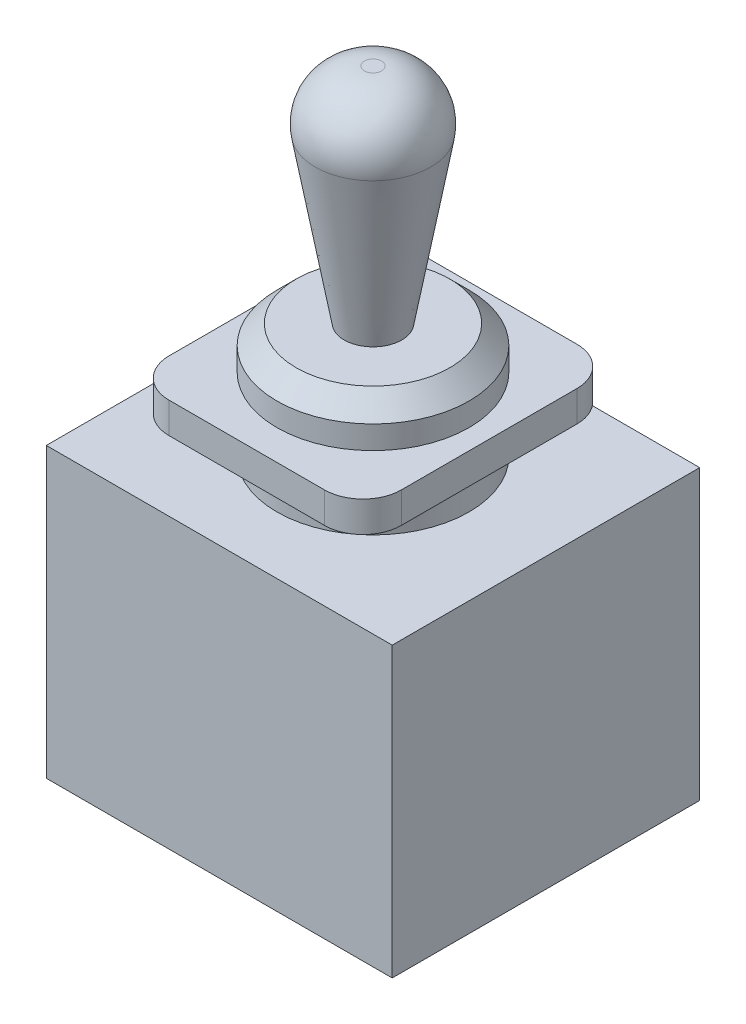
SolidWorks part; units mm, degrees
ref_plane "Спереди" through (0, 0, 0) normal (0, 0, 1) x (1, 0, 0)
ref_plane "Сверху" through (0, 0, 0) normal (0, 1, 0) x (1, 0, 0)
ref_plane "Справа" through (0, 0, 0) normal (1, 0, 0) x (0, 0, -1)
sketch "Эскиз1" plane through (0, 0, 0) normal (0, 1, 0) x (1, 0, 0)
  line L1 (-4.5, 4) -> (4.5, 4)
  line L2 (-4.5, 4) -> (-4.5, -4)
  line L3 (-4.5, -4) -> (4.5, -4)
  line L4 (4.5, 4) -> (4.5, -4)
  line L5 (0, -4) -> (0, 4) construction
  line L6 (-4.5, 0) -> (4.5, 0) construction
  point P0 (0, 0)
  dimension "D1" = 9
  dimension "D2" = 8
extrude "Бобышка-Вытянуть1" add sketch "Эскиз1" along normal mid plane 7.5
sketch "Эскиз2" plane through (0, 3.75, 0) normal (0, 1, 0) x (1, 0, 0)
  circle A1 centre (0, 0) radius 2.5
  dimension "D1" = 5
extrude "Бобышка-Вытянуть2" add sketch "Эскиз2" along normal blind 3
chamfer "Фаска1" distance 0.5 angle 45 1 edges at (0, 6.75, 2.5)
ref_plane "Плоскость1" through (0, 5.65, 0) normal (0, 1, 0) x (1, 0, 0)
sketch "Эскиз3" plane through (0, 5.65, 0) normal (0, 1, 0) x (1, 0, 0)
  line L1 (-2.021, -3.2833) -> (2.021, -3.2833)
  line L2 (-3.021, -2.2833) -> (-3.021, 2.2833)
  line L4 (3.021, -2.2833) -> (3.021, 2.2833)
  line L5 (0, 2.8868) -> (0, -3.2833) construction
  line L6 (-3.021, 0) -> (3.021, 0) construction
  line L7 (-2.021, 3.2833) -> (2.021, 3.2833)
  arc A0 (-2.021, -3.2833) -> (-3.021, -2.2833) centre (-2.021, -2.2833) cw
  arc A1 (3.021, -2.2833) -> (2.021, -3.2833) centre (2.021, -2.2833) cw
  arc A2 (3.021, 2.2833) -> (2.021, 3.2833) centre (2.021, 2.2833) ccw
  arc A3 (-3.021, 2.2833) -> (-2.021, 3.2833) centre (-2.021, 2.2833) cw
  point P0 (0, 0)
  dimension "D1" = 1
extrude "Бобышка-Вытянуть3" add sketch "Эскиз3" against normal blind 0.8
sketch "Эскиз4" plane through (0, 6.75, 0) normal (0, 1, 0) x (1, 0, 0)
  circle A0 centre (0, 0) radius 0.75
  dimension "D1" = 1.5
extrude "Бобышка-Вытянуть4" add sketch "Эскиз4" along normal blind 5.8 draft 10 draft outward yes
fillet "Скругление1" radius 1.3 1 edges at (0, 12.55, 1.7727)
